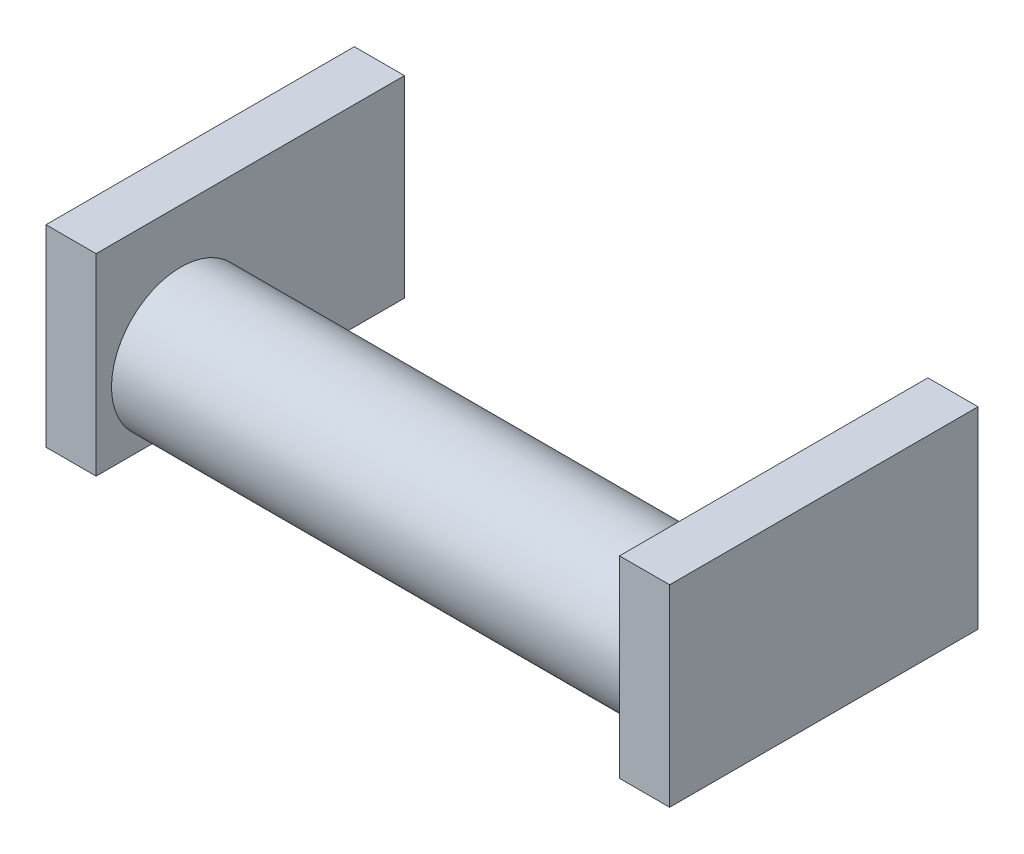
SolidWorks part; units mm, degrees
ref_plane "Front Plane" through (0, 0, 0) normal (0, 0, 1) x (1, 0, 0)
ref_plane "Top Plane" through (0, 0, 0) normal (0, 1, 0) x (1, 0, 0)
ref_plane "Right Plane" through (0, 0, 0) normal (1, 0, 0) x (0, 0, -1)
sketch "Sketch1" plane through (0, 0, 0) normal (0, 0, 1) x (1, 0, 0)
  line L0 (-33.7, -12.65) -> (-33.7, -70.9) construction
  line L1 (-33.7, -50.4) -> (-40.2, -50.4)
  line L2 (-33.7, -50.4) -> (-33.7, -75.4)
  line L3 (-33.7, -75.4) -> (-40.2, -75.4)
  line L4 (-40.2, -50.4) -> (-40.2, -75.4)
  line L5 (-30, -75.4) -> (-27.3083, -75.4) construction
  line L6 (-40.2, -70.9) -> (-40.2, -3.15) construction
  circle A0 centre (-37.2, -55.4) radius 1.65 construction
  dimension "D1" = 5
extrude "Boss-Extrude1" add sketch "Sketch1" along normal blind 40
sketch "Sketch2" plane through (0, 0, 0) normal (0, 0, -1) x (-1, 0, 0)
  circle A0 centre (37.2, -55.4) radius 1.25
  circle A1 centre (37.2, -64) radius 1.25
  dimension "D1" = 2.5
extrude "Cut-Extrude1" cut sketch "Sketch2" against normal blind 10
sketch "Sketch3" plane through (-33.7, 0, 0) normal (1, 0, 0) x (0, 0, -1)
  line L0 (-40, -75.4) -> (0, -75.4) construction
  circle A0 centre (-29, -66.4) radius 9
extrude "Boss-Extrude2" add sketch "Sketch3" along normal up to surface (67.9 mm away)
ref_plane "Plane1" through (0.25, 0, 0) normal (1, 0, 0) x (0, 0, -1)
mirror "Mirror1" about plane through (0.25, 0, 0) normal (1, 0, 0) of "Cut-Extrude1", "Boss-Extrude1"
